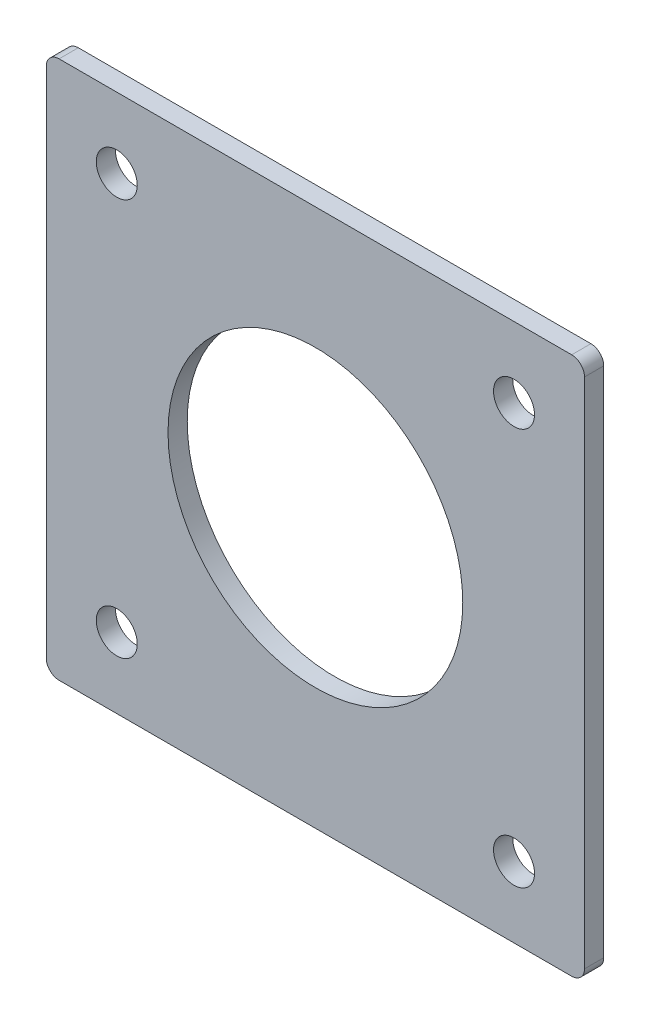
SolidWorks part; units mm, degrees
ref_plane "前视基准面" through (0, 0, 0) normal (0, 0, 1) x (1, 0, 0)
ref_plane "上视基准面" through (0, 0, 0) normal (0, 1, 0) x (1, 0, 0)
ref_plane "右视基准面" through (0, 0, 0) normal (1, 0, 0) x (0, 0, -1)
sketch "草图1" plane through (0, 0, 0) normal (0, 0, 1) x (1, 0, 0)
  line L0 (-23.1418, 26.4851) -> (-23.1418, -15.5149) construction
  line L1 (-44.1418, 26.4851) -> (-2.1418, 26.4851)
  line L2 (-44.1418, 26.4851) -> (-44.1418, -15.5149)
  line L3 (-44.1418, -15.5149) -> (-2.1418, -15.5149)
  line L4 (-2.1418, 26.4851) -> (-2.1418, -15.5149)
  line L5 (-44.1418, 5.4851) -> (-2.1418, 5.4851) construction
  circle A0 centre (-38.6418, 20.9851) radius 1.6
  circle A1 centre (-23.1418, 5.4851) radius 11.5
  circle A2 centre (-7.6418, 20.9851) radius 1.6
  circle A3 centre (-7.6418, -10.0149) radius 1.6
  circle A4 centre (-38.6418, -10.0149) radius 1.6
  dimension "D3" = 3.2
  dimension "D4" = 23
  dimension "D5" = 21
  dimension "D6" = 21
  dimension "D7" = 15.5
  dimension "D8" = 15.5
  dimension "D1" = 42
  dimension "D2" = 42
extrude "凸台-拉伸1" add sketch "草图1" along normal blind 1.5
fillet "圆角1" radius 1 4 edges at (-44.1418, -15.5149, 0.75) (-2.1418, -15.5149, 0.75) (-44.1418, 26.4851, 0.75) (-2.1418, 26.4851, 0.75)
